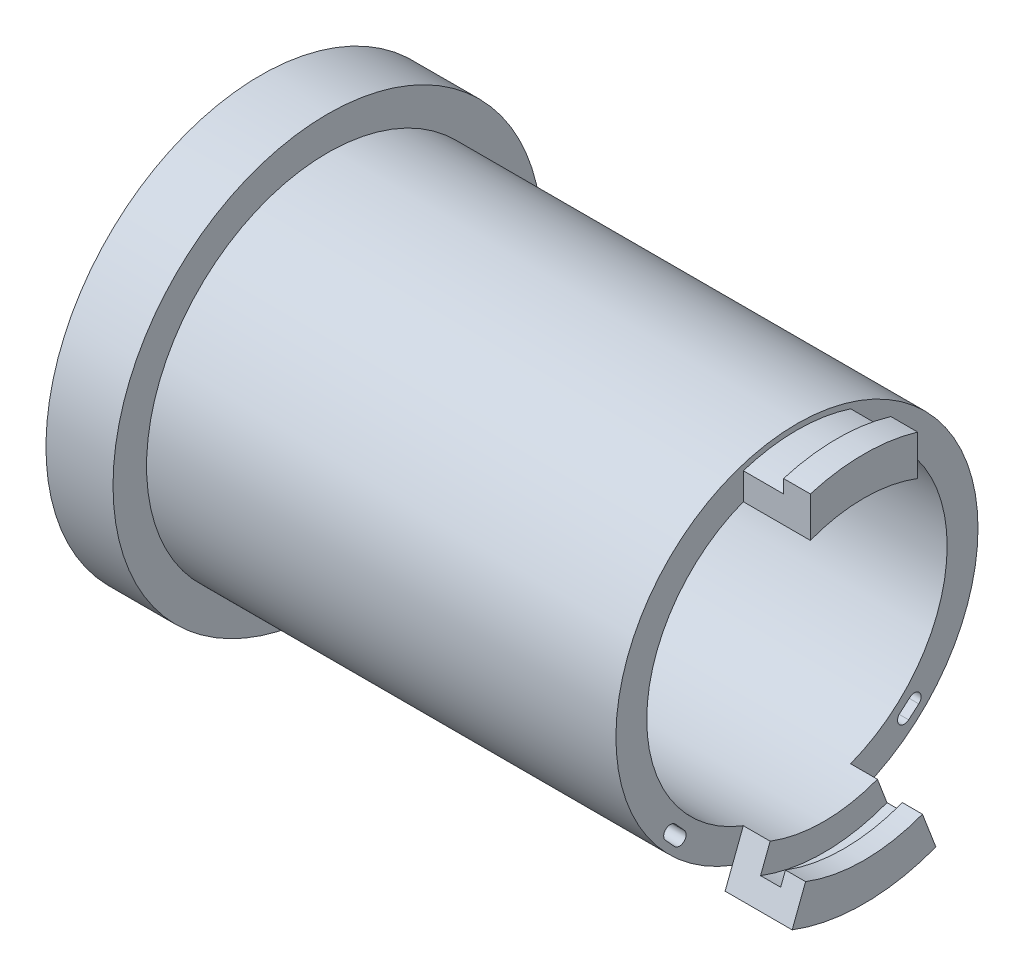
SolidWorks part; units mm, degrees
material "ABS"
ref_plane "Front Plane" through (0, 0, 0) normal (0, 0, 1) x (1, 0, 0)
ref_plane "Top Plane" through (0, 0, 0) normal (0, 1, 0) x (1, 0, 0)
ref_plane "Right Plane" through (0, 0, 0) normal (1, 0, 0) x (0, 0, -1)
sketch "Sketch1" plane through (0, 0, 0) normal (1, 0, 0) x (0, 0, -1)
  circle A0 centre (0, 0) radius 16
  dimension "D1" = 32
extrude "Boss-Extrude1" add sketch "Sketch1" along normal blind 40
sketch "Sketch2" plane through (40, 0, 0) normal (1, 0, 0) x (0, 0, -1)
  circle A0 centre (0, 0) radius 11.2
  dimension "D1" = 22.4
extrude "Cut-Extrude1" cut sketch "Sketch2" against normal through all
sketch "Sketch3" plane through (40, 0, 0) normal (1, 0, 0) x (0, 0, -1)
  circle A0 centre (0, 0) radius 13.5
  dimension "D1" = 27
extrude "Cut-Extrude2" cut sketch "Sketch3" against normal blind 35 flip side to cut contours A0
sketch "Sketch4" plane through (0, 0, 0) normal (-1, 0, 0) x (0, 0, 1)
  line L4 (-4, 10.4614) -> (-4, 13.4614)
  line L5 (4, 10.4614) -> (4, 13.4614)
  arc A1 (-4, 10.4614) -> (4, 10.4614) centre (0, 0) cw
  circle A3 centre (0, 0) radius 11.2 construction
  arc A4 (-4, 13.4614) -> (4, 13.4614) centre (0, 0) cw
  point P7 (0, 11.2)
  dimension "D1" = 4
  dimension "D2" = 4
  dimension "D3" = 3
extrude "Cut-Extrude3" cut sketch "Sketch4" against normal blind 3
sketch "Sketch11" plane through (0, 0, 0) normal (-1, 0, 0) x (0, 0, 1)
  line L0 (-4, -12.2042) -> (-4.9833, -15.2042)
  line L1 (4, -12.2042) -> (4.9833, -15.2042)
  arc A0 (-4, -12.2042) -> (4, -12.2042) centre (0, 0) ccw
  circle A1 centre (0, 0) radius 16 construction
  circle A2 centre (0, 0) radius 11.2 construction
  point P4 (0, -11.2)
  point P9 (0, 0)
  dimension "D1" = 4
  dimension "D2" = 3
  dimension "D3" = 4
extrude "Cut-Extrude9" cut sketch "Sketch11" against normal blind 3 and the other way through all flip side to cut
sketch "Sketch15" plane through (0, 0, 0) normal (-1, 0, 0) x (0, 0, 1)
  line L0 (-4, 13.4614) -> (-4, 10.4614) construction
  line L4 (-4, -12.2042) -> (-4.3278, -13.2042)
  line L5 (-4, -12.2042) -> (-4.9833, -15.2042) construction
  line L7 (4, -12.2042) -> (4.3278, -13.2042)
  line L8 (4, 10.4614) -> (4, 13.4614) construction
  line L9 (4.9833, -15.2042) -> (4, -12.2042) construction
  line L11 (-4, 12.4614) -> (-4, 13.4614)
  line L12 (4, 12.4614) -> (4, 13.4614)
  arc A2 (-4, -12.2042) -> (4, -12.2042) centre (0, 0) ccw
  arc A3 (-4, -12.2042) -> (4, -12.2042) centre (0, 0) ccw construction
  arc A4 (-4.3278, -13.2042) -> (4.3278, -13.2042) centre (0, 0) ccw
  arc A6 (-4, 12.4614) -> (4, 12.4614) centre (0, 0) cw
  arc A8 (-4, 13.4614) -> (4, 13.4614) centre (0, 0) cw
  arc A9 (4, 13.4614) -> (-4, 13.4614) centre (0, 0) ccw construction
  dimension "D1" = 1
  dimension "D2" = 1
extrude "Boss-Extrude3" add sketch "Sketch15" against normal blind 1.5
sketch "Sketch16" plane through (40, 0, 0) normal (1, 0, 0) x (0, 0, -1)
  line L0 (-4, 10.4614) -> (-4, 13.4614)
  line L1 (4, 10.4614) -> (4, 13.4614)
  line L2 (-4, -10.4614) -> (-5.3571, -14.0107)
  line L3 (4, -10.4614) -> (5.3571, -14.0107)
  circle A0 centre (0, 0) radius 11.2 construction
  arc A2 (-4, 10.4614) -> (4, 10.4614) centre (0, 0) cw
  arc A3 (-4, 13.4614) -> (4, 13.4614) centre (0, 0) cw
  arc A4 (-4, -10.4614) -> (4, -10.4614) centre (0, 0) ccw
  arc A5 (-5.3571, -14.0107) -> (5.3571, -14.0107) centre (0, 0) ccw
  point P0 (0, 11.2)
  point P1 (0, -11.2)
  dimension "D3" = 3
  dimension "D1" = 4
  dimension "D2" = 4
  dimension "D4" = 4
  dimension "D5" = 4
  dimension "D6" = 3.8
extrude "Boss-Extrude4" add sketch "Sketch16" along normal blind 5
sketch "Sketch17" plane through (40, 0, 0) normal (1, 0, 0) x (0, 0, -1)
  line L0 (-4, 13.4614) -> (-4, 12.4614)
  line L1 (-4, 13.4614) -> (-4, 10.4614) construction
  line L2 (4, 13.4614) -> (4, 12.4614)
  line L3 (4, 10.4614) -> (4, 13.4614) construction
  arc A0 (-4, 13.4614) -> (4, 13.4614) centre (0, 0) cw
  arc A1 (4, 13.4614) -> (-4, 13.4614) centre (0, 0) ccw construction
  arc A2 (-4, 12.4614) -> (4, 12.4614) centre (0, 0) cw
  dimension "D1" = 1
extrude "Cut-Extrude10" cut sketch "Sketch17" along normal blind 3
sketch "Sketch18" plane through (45, 0, 0) normal (1, 0, 0) x (0, 0, -1)
  line L0 (5.3571, -14.0107) -> (4, -10.4614) construction
  line L1 (-4, -10.4614) -> (-4.7143, -12.3295)
  line L2 (-4, -10.4614) -> (-5.3571, -14.0107) construction
  line L3 (4, -10.4614) -> (4.7143, -12.3295)
  arc A0 (-4, -10.4614) -> (4, -10.4614) centre (0, 0) ccw
  arc A1 (-4.7143, -12.3295) -> (4.7143, -12.3295) centre (0, 0) ccw
  dimension "D1" = 2
extrude "Cut-Extrude11" cut sketch "Sketch18" against normal blind 3
sketch "Sketch21" plane through (45, 0, 0) normal (1, 0, 0) x (0, 0, -1)
  line L6 (4.7143, -12.3295) -> (4, -10.4614) construction
  line L7 (-4.7143, -12.3295) -> (-4.3571, -11.3954)
  line L8 (-4, -10.4614) -> (-4.7143, -12.3295) construction
  line L9 (4.7143, -12.3295) -> (4.3571, -11.3954)
  arc A4 (-4.7143, -12.3295) -> (4.7143, -12.3295) centre (0, 0) ccw
  arc A5 (-4.3571, -11.3954) -> (4.3571, -11.3954) centre (0, 0) ccw
  dimension "D1" = 1
extrude "Boss-Extrude5" add sketch "Sketch21" against normal blind 1.5
sketch "Sketch22" plane through (40, 0, 0) normal (1, 0, 0) x (0, 0, -1)
  line L0 (0, 0) -> (8.7449, -10.2847) construction
  line L1 (8, -9.4086) -> (8.7574, -8.7556) construction
  line L2 (7.6735, -9.03) -> (8.4309, -8.377)
  line L3 (8.3265, -9.7873) -> (9.0839, -9.1343)
  line L5 (-8.7642, -8.903) -> (-9.4358, -8.162) construction
  line L6 (-9.1347, -9.2388) -> (-9.8063, -8.4978)
  line L7 (-8.3937, -8.5673) -> (-9.0653, -7.8263)
  arc A0 (4.8214, -12.6097) -> (-4.8214, -12.6097) centre (0, 0) ccw construction
  arc A1 (4, -10.4614) -> (4, 10.4614) centre (0, 0) ccw construction
  arc A3 (-9.1347, -9.2388) -> (-8.3937, -8.5673) centre (-8.7642, -8.903) ccw
  arc A4 (7.6735, -9.03) -> (8.3265, -9.7873) centre (8, -9.4086) ccw
  arc A5 (9.0839, -9.1343) -> (8.4309, -8.377) centre (8.7574, -8.7556) ccw
  arc A6 (-9.0653, -7.8263) -> (-9.8063, -8.4978) centre (-9.4358, -8.162) ccw
  point P6 (7.2551, -8.5325)
  point P7 (8, -9.4086)
  point P11 (8, -9.4086)
  point P12 (8.3787, -9.0821)
  point P21 (-9.1, -8.5325)
  dimension "D4" = 1
  dimension "D1" = 1.15
  dimension "D2" = 1.15
  dimension "D3" = 8
  dimension "D5" = 1
  dimension "D6" = 1
  dimension "D7" = 1
  dimension "D8" = 5.1
extrude "Cut-Extrude12" cut sketch "Sketch22" against normal through all
sketch "Sketch23" plane through (0, 0, 0) normal (-1, 0, 0) x (0, 0, 1)
  line L0 (9.7715, -7.7916) -> (10.9855, -8.6727)
  line L1 (-9.136, -8.4291) -> (-10.202, -9.582)
  line L2 (-7.5026, -9.3575) -> (-9.136, -8.4291)
  line L3 (8.3937, -8.5673) -> (9.7715, -7.7916)
  arc A0 (8.3937, -8.5673) -> (-7.5026, -9.3575) centre (0, 0) cw
  arc A1 (-8.3265, -9.7873) -> (-7.6735, -9.03) centre (-8, -9.4086) ccw construction
  arc A2 (9.8063, -8.4978) -> (9.0653, -7.8263) centre (9.4358, -8.162) ccw construction
  arc A3 (10.9855, -8.6727) -> (-10.202, -9.582) centre (0, 0) cw
  arc A4 (-8.4309, -8.377) -> (-9.0839, -9.1343) centre (-8.7574, -8.7556) ccw construction
  dimension "D1" = 1.5
extrude "Cut-Extrude13" cut sketch "Sketch23" against normal blind 1
